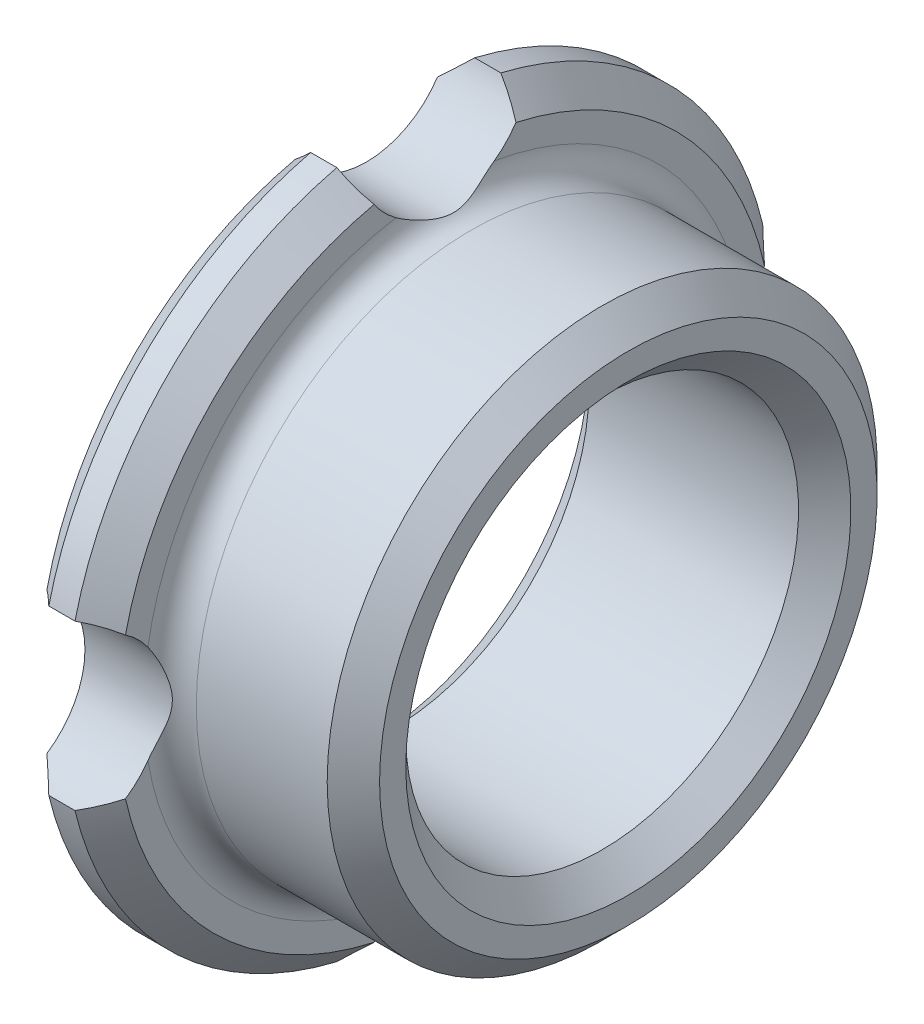
SolidWorks part; units mm, degrees
material "Phosphor bronze 10% D, UNS C52400"
ref_plane "Front Plane" through (0, 0, 0) normal (0, 0, 1) x (1, 0, 0)
ref_plane "Top Plane" through (0, 0, 0) normal (0, 1, 0) x (1, 0, 0)
ref_plane "Right Plane" through (0, 0, 0) normal (1, 0, 0) x (0, 0, -1)
sketch "Sketch1" plane through (0, 0, 0) normal (0, 0, 1) x (1, 0, 0)
  line L0 (0, 7.5) -> (10, 7.5)
  line L1 (10, 7.5) -> (10, 10.5)
  line L2 (10, 10.5) -> (3, 10.5)
  line L3 (3, 10.5) -> (3, 13.5)
  line L4 (3, 13.5) -> (0, 13.5)
  line L5 (0, 13.5) -> (0, 7.5)
  line L6 (0, 0) -> (44.8454, 0) construction
  dimension "D1" = 15
  dimension "D2" = 3
  dimension "D3" = 27
  dimension "D4" = 10
  dimension "D5" = 21
revolve "Revolve1" add sketch "Sketch1" angle 360 about L6
chamfer "Chamfer1" distance 1 angle 45 5 edges at (0, 0, 7.5) (10, 0, 7.5) (3, 0, 13.5) (0, 0, 13.5) (10, 0, 10.5)
fillet "Fillet1" radius 1 1 edges at (3, 0, 10.5)
sketch "Sketch2" plane through (0, 0, 0) normal (-1, 0, 0) x (0, 0, 1)
  line L0 (-14, 0) -> (14, 0) construction
  line L1 (14, 0) -> (0, 14) construction
  line L2 (0, 14) -> (0, -14) construction
  circle A0 centre (0, 14) radius 3.25
  circle A1 centre (-14, 0) radius 3.25
  circle A2 centre (0, -14) radius 3.25
  circle A3 centre (14, 0) radius 3.25
  point P8 (0, 0)
  dimension "D1" = 6.5
  dimension "D2" = 28
extrude "Cut-Extrude1" cut sketch "Sketch2" against normal blind 10
move or copy body "Body-Move/Copy1" [suppressed] bodies to move or copy 101
